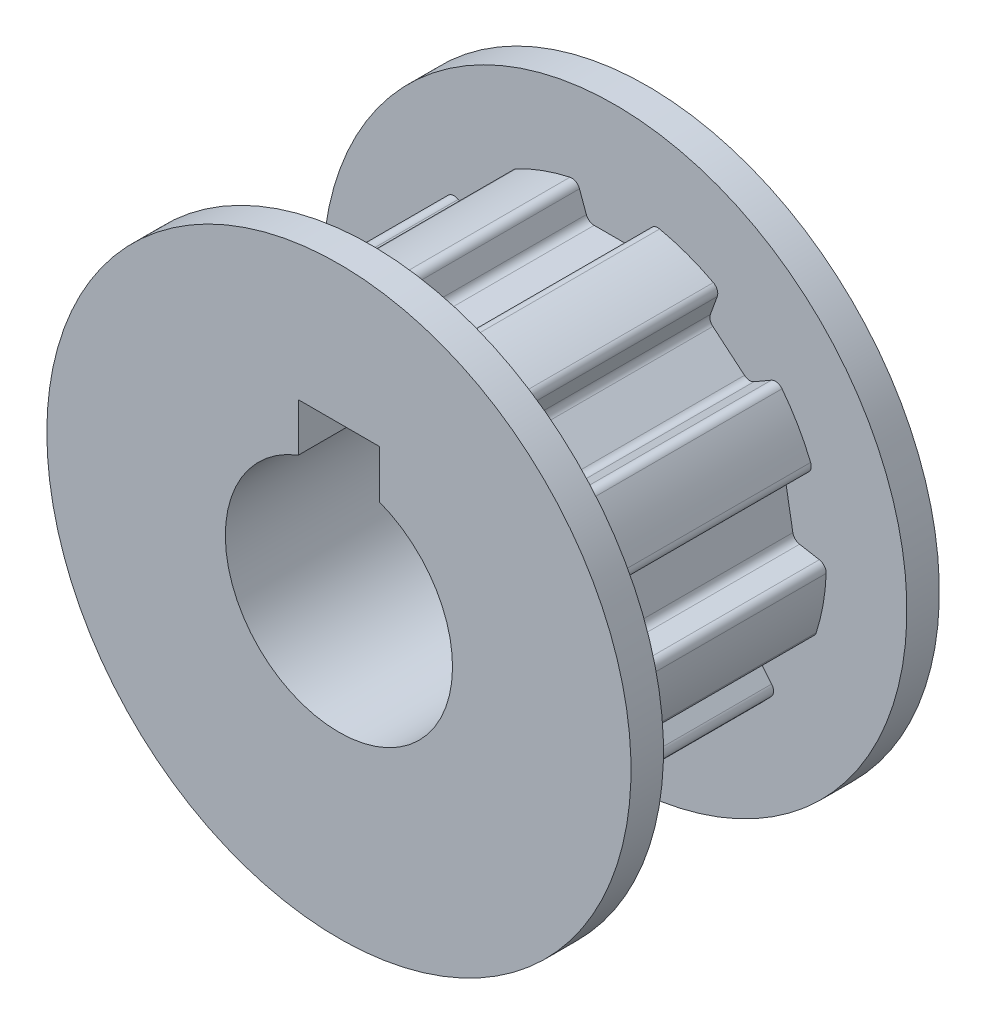
SolidWorks part; units mm, degrees
ref_plane "Front Plane" through (0, 0, 0) normal (0, 0, 1) x (1, 0, 0)
ref_plane "Top Plane" through (0, 0, 0) normal (0, 1, 0) x (1, 0, 0)
ref_plane "Right Plane" through (0, 0, 0) normal (1, 0, 0) x (0, 0, -1)
sketch "Sketch1" plane through (0, 0, 0) normal (0, 1, 0) x (1, 0, 0)
  line L0 (0, 36.1296) -> (0, -19.4741) construction
sketch "Sketch2" plane through (0, 0, 0) normal (0, 1, 0) x (1, 0, 0)
  line L11 (7, -9.5) -> (7, 9.5)
  line L12 (0, 0) -> (7, 0) construction
  line L14 (7, 9.5) -> (18, 9.5)
  line L15 (18, 9.5) -> (18, 7.5)
  line L16 (18, 7.5) -> (11, 7.5)
  line L17 (11, 7.5) -> (11, -7.5)
  line L18 (11, -7.5) -> (18, -7.5)
  line L19 (18, -7.5) -> (18, -9.5)
  line L20 (18, -9.5) -> (7, -9.5)
  dimension "D1" = 7
  dimension "D3" = 2
  dimension "D4" = 15
  dimension "D5" = 18
  dimension "D6" = 7
  dimension "2" = 2
revolve "Revolve1" add sketch "Sketch2" angle 360 about L0
sketch "Sketch3" plane through (0, 0, 0) normal (0, 0, 1) x (1, 0, 0)
  line L0 (0, 0) -> (0, 9.5) construction
  line L1 (-2.5, 0) -> (2.5, 0)
  line L2 (-2.5, 0) -> (-2.5, 9.5)
  line L3 (-2.5, 9.5) -> (2.5, 9.5)
  line L4 (2.5, 0) -> (2.5, 9.5)
  line L5 (0, 9.5) -> (0, 18) construction
  circle A1 centre (0, 0) radius 18 construction
  dimension "D1" = 8.5
  dimension "D2" = 5
extrude "Cut-Extrude1" cut sketch "Sketch3" against normal through all both and the other way through all
sketch "Sketch4" plane through (0, 0, 0) normal (0, 0, 1) x (1, 0, 0)
  line L0 (0, 0) -> (0, 11.8728) construction
  line L1 (-2.325, 12.8278) -> (-2.9401, 14.5178) construction
  line L2 (-2.325, 12.8278) -> (-1.6298, 10.9178) construction
  line L3 (-1.6298, 10.9178) -> (1.6298, 10.9178) construction
  line L4 (1.6298, 10.9178) -> (2.325, 12.8278) construction
  line L5 (2.325, 12.8278) -> (-2.325, 12.8278) construction
  line L6 (0, 10.9178) -> (0, 12.8278) construction
  line L7 (-2.9401, 14.5178) -> (2.9401, 14.5178) construction
  line L8 (2.9401, 14.5178) -> (2.325, 12.8278) construction
  line L9 (0, 14.8125) -> (0, 13.0368) construction
  line L10 (0, 13.0368) -> (0, 12.8278) construction
  line L11 (0, 0) -> (7.6317, 9.0951) construction
  line L12 (7.6317, 9.0951) -> (8.3799, 9.9867) construction
  line L13 (8.3799, 9.9867) -> (9.5213, 11.347) construction
  line L14 (0, 13.9246) -> (8.9506, 10.6669) construction
  circle A0 centre (0, 0) radius 11
  circle A1 centre (0, 0) radius 11.8728 construction
  circle A2 centre (-1.2727, 11.4278) radius 0.51 construction
  circle A3 centre (1.2727, 11.4278) radius 0.51 construction
  circle A4 centre (0, 0) radius 13.0368
  circle A5 centre (0, 0) radius 14.8125 construction
  dimension "D3" = 40
  dimension "D6" = 1.02
  dimension "D1" = 40
  dimension "D2" = 22
  dimension "D7" = 3.6
  dimension "D8" = 9.525
  dimension "D4" = 1.91
  dimension "D5" = 4.65
extrude "Boss-Extrude1" add sketch "Sketch4" along normal up to next and the other way up to next
sketch "Sketch5" plane through (0, 0, 0) normal (0, 0, 1) x (1, 0, 0)
  line L0 (-1.6298, 10.9178) -> (1.6298, 10.9178)
  line L1 (1.6298, 10.9178) -> (2.4011, 13.0368)
  line L2 (2.4011, 13.0368) -> (-2.4011, 13.0368)
  line L3 (-2.4011, 13.0368) -> (-1.6298, 10.9178)
  line L4 (-2.325, 12.8278) -> (-1.6298, 10.9178) construction
  line L5 (1.6298, 10.9178) -> (2.325, 12.8278) construction
  line L6 (5.7693, 9.4111) -> (8.2663, 7.3159)
  line L7 (8.2663, 7.3159) -> (10.2192, 8.4434)
  line L8 (10.2192, 8.4434) -> (6.5405, 11.5301)
  line L9 (6.5405, 11.5301) -> (5.7693, 9.4111)
  line L10 (10.4689, 3.5009) -> (11.0349, 0.2908)
  line L11 (11.0349, 0.2908) -> (13.2556, -0.1008)
  line L12 (13.2556, -0.1008) -> (12.4218, 4.6284)
  line L13 (12.4218, 4.6284) -> (10.4689, 3.5009)
  line L14 (10.27, -4.0474) -> (8.6401, -6.8703)
  line L15 (8.6401, -6.8703) -> (10.0896, -8.5978)
  line L16 (10.0896, -8.5978) -> (12.4907, -4.439)
  line L17 (12.4907, -4.439) -> (10.27, -4.0474)
  line L18 (5.2656, -9.7019) -> (2.2026, -10.8168)
  line L19 (2.2026, -10.8168) -> (2.2026, -13.0718)
  line L20 (2.2026, -13.0718) -> (6.7151, -11.4293)
  line L21 (6.7151, -11.4293) -> (5.2656, -9.7019)
  line L22 (-2.2026, -10.8168) -> (-5.2656, -9.7019)
  line L23 (-5.2656, -9.7019) -> (-6.7151, -11.4293)
  line L24 (-6.7151, -11.4293) -> (-2.2026, -13.0718)
  line L25 (-2.2026, -13.0718) -> (-2.2026, -10.8168)
  line L26 (-8.6401, -6.8703) -> (-10.27, -4.0474)
  line L27 (-10.27, -4.0474) -> (-12.4907, -4.439)
  line L28 (-12.4907, -4.439) -> (-10.0896, -8.5978)
  line L29 (-10.0896, -8.5978) -> (-8.6401, -6.8703)
  line L30 (-11.0349, 0.2908) -> (-10.4689, 3.5009)
  line L31 (-10.4689, 3.5009) -> (-12.4218, 4.6284)
  line L32 (-12.4218, 4.6284) -> (-13.2556, -0.1008)
  line L33 (-13.2556, -0.1008) -> (-11.0349, 0.2908)
  line L34 (-8.2663, 7.3159) -> (-5.7693, 9.4111)
  line L35 (-5.7693, 9.4111) -> (-6.5405, 11.5301)
  line L36 (-6.5405, 11.5301) -> (-10.2192, 8.4434)
  line L37 (-10.2192, 8.4434) -> (-8.2663, 7.3159)
  circle A0 centre (0, 0) radius 13.0368 construction
  point P47 (0, 0)
  dimension "D1" = 9
extrude "Cut-Extrude2" cut sketch "Sketch5" against normal up to surface and the other way up to surface up to face at (-13.0368, 0, -7.5) other way up to face at (13.0368, 0, 7.5)
fillet "Fillet1" radius 0.51 36 edges at (-5.7693, 9.4111, 0) (-8.2663, 7.3159, 0) (-10.0266, 8.3322, 0) (-12.2291, 4.5172, 0) (-10.4689, 3.5009, 0) (-11.0349, 0.2908, 0) (-13.0366, -0.0622, 0) (-12.2717, -4.4004, 0) (-10.27, -4.0474, 0) (-8.6401, -6.8703, 0) (-9.9467, -8.4274, 0) (-6.5721, -11.259, 0) (-5.2656, -9.7019, 0) (-2.2026, -10.8168, 0) (-2.2026, -12.8493, 0) (2.2026, -12.8493, 0) (2.2026, -10.8168, 0) (5.2656, -9.7019, 0) (6.5721, -11.259, 0) (9.9467, -8.4274, 0) (8.6401, -6.8703, 0) (10.27, -4.0474, 0) (12.2717, -4.4004, 0) (13.0366, -0.0622, 0) (11.0349, 0.2908, 0) (10.4689, 3.5009, 0) (12.2291, 4.5172, 0) (10.0266, 8.3322, 0) (8.2663, 7.3159, 0) (5.7693, 9.4111, 0) (2.325, 12.8278, 0) (1.6298, 10.9178, 0) (-1.6298, 10.9178, 0) (-2.325, 12.8278, 0) (-6.4645, 11.3211, 0) (6.4645, 11.3211, 0)
